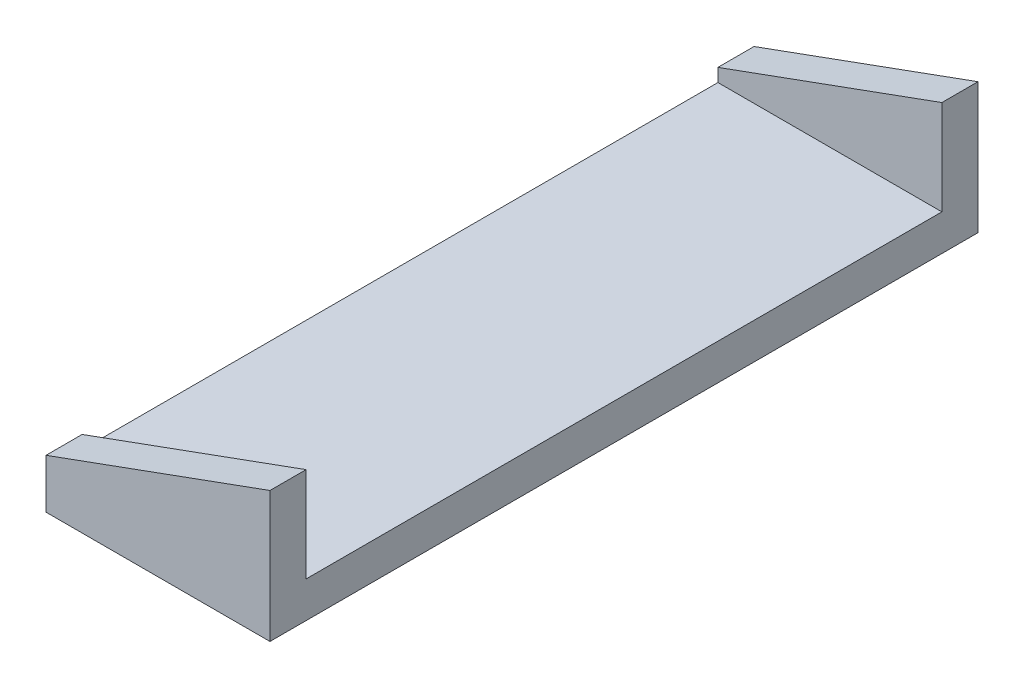
SolidWorks part; units mm, degrees
ref_plane "Front Plane" through (0, 0, 0) normal (0, 0, 1) x (1, 0, 0)
ref_plane "Top Plane" through (0, 0, 0) normal (0, 1, 0) x (1, 0, 0)
ref_plane "Right Plane" through (0, 0, 0) normal (1, 0, 0) x (0, 0, -1)
sketch "Sketch1" plane through (0, 0, 0) normal (0, 1, 0) x (1, 0, 0)
  line L1 (0, 0) -> (457.2, 0)
  line L2 (0, 0) -> (0, 1244.6)
  line L3 (0, 1244.6) -> (457.2, 1244.6)
  line L4 (457.2, 0) -> (457.2, 1244.6)
extrude "Boss-Extrude1" add sketch "Sketch1" along normal blind 63.5
sketch "Sketch4" plane through (0, 63.5, 0) normal (0, 1, 0) x (1, 0, 0)
  line L0 (0, 1244.6) -> (0, 0) construction
  line L1 (457.2, 1244.6) -> (0, 1244.6)
  line L2 (457.2, 1244.6) -> (457.2, 1181.1)
  line L3 (457.2, 1181.1) -> (0, 1181.1)
  line L4 (0, 1244.6) -> (0, 1181.1)
  line L6 (457.2, 0) -> (0, 0)
  line L7 (457.2, 0) -> (457.2, 63.5)
  line L8 (457.2, 63.5) -> (0, 63.5)
  line L9 (0, 0) -> (0, 63.5)
extrude "Boss-Extrude2" add sketch "Sketch4" along normal blind 266.7 contours L2 L1 L4 L3
sketch "Sketch6" plane through (0, 63.5, 0) normal (0, 1, 0) x (1, 0, 0)
  line L1 (0, 0) -> (304.8, 0)
  line L2 (0, 0) -> (0, 63.5)
  line L3 (0, 63.5) -> (304.8, 63.5)
  line L4 (304.8, 0) -> (304.8, 63.5)
ref_plane "Plane3" through (0, 0, -622.3) normal (0, 0, -1) x (-1, 0, 0)
sketch "Sketch10" plane through (0, 0, -1181.1) normal (0, 0, 1) x (1, 0, 0)
  line L0 (0, 63.5) -> (457.2, 229.9072)
  line L2 (457.2, 330.2) -> (457.2, 63.5) construction
  line L3 (0, 63.5) -> (0, 330.2)
  line L4 (0, 330.2) -> (457.2, 330.2)
  line L5 (457.2, 330.2) -> (457.2, 229.9072)
sketch "Sketch11" plane through (0, 0, -1181.1) normal (0, 0, 1) x (1, 0, 0)
  line L0 (0, 63.5) -> (0, 330.2)
  line L1 (0, 330.2) -> (457.2, 330.2)
  line L2 (457.2, 330.2) -> (457.2, 229.9072)
  line L6 (457.2, 229.9072) -> (0, 63.5)
mirror "Mirror7" about plane through (0, 0, -622.3) normal (0, 0, -1) of "Boss-Extrude2"
extrude "Cut-Extrude7" cut sketch "Sketch11" against normal blind 100.076
mirror "Mirror8" about plane through (0, 0, -622.3) normal (0, 0, -1) of "Cut-Extrude7"
sketch "Sketch12" plane through (0, 0, 0) normal (0, -1, 0) x (1, 0, 0)
  line L1 (0, -1244.6) -> (457.2, -1244.6) construction
  line L2 (0, 0) -> (63.5, 0)
  line L3 (0, 0) -> (0, -1244.6)
  line L4 (0, -1244.6) -> (63.5, -1244.6)
  line L5 (63.5, 0) -> (63.5, -1244.6)
extrude "Cut-Extrude8" cut sketch "Sketch12" against normal blind 253.746
